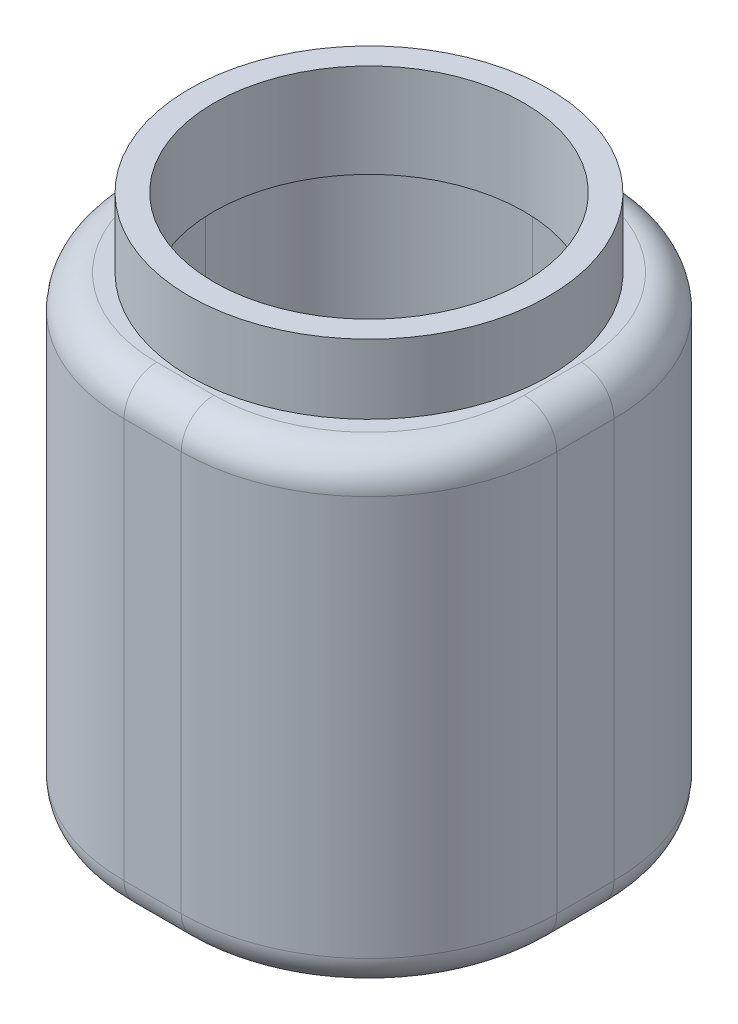
SolidWorks part; units mm, degrees
material "Glass"
ref_plane "Front Plane" through (0, 0, 0) normal (0, 0, 1) x (1, 0, 0)
ref_plane "Top Plane" through (0, 0, 0) normal (0, 1, 0) x (1, 0, 0)
ref_plane "Right Plane" through (0, 0, 0) normal (1, 0, 0) x (0, 0, -1)
sketch "Sketch1" plane through (0, 0, 0) normal (0, 1, 0) x (1, 0, 0)
  line L1 (-67.31, 67.31) -> (67.31, 67.31)
  line L2 (-67.31, 67.31) -> (-67.31, -67.31)
  line L3 (-67.31, -67.31) -> (67.31, -67.31)
  line L4 (67.31, 67.31) -> (67.31, -67.31)
  line L5 (-67.31, 67.31) -> (67.31, -67.31) construction
  line L6 (-67.31, -67.31) -> (67.31, 67.31) construction
  point P0 (0, 0)
  dimension "D1" = 134.62
extrude "Boss-Extrude1" add sketch "Sketch1" along normal blind 144.78
fillet "Fillet1" radius 58.42 4 edges at (67.31, 72.39, 67.31) (-67.31, 72.39, 67.31) (67.31, 72.39, -67.31) (-67.31, 72.39, -67.31)
fillet "Fillet2" radius 10.16 16 edges at (0, 144.78, -67.31) (50.1992, 144.78, -50.1992) (67.31, 144.78, 0) (50.1992, 144.78, 50.1992) (0, 144.78, 67.31) (-50.1992, 144.78, 50.1992) (-67.31, 144.78, 0) (-67.31, 0, 0) (-50.1992, 0, 50.1992) (0, 0, 67.31) (50.1992, 0, 50.1992) (67.31, 0, 0) (50.1992, 0, -50.1992) (0, 0, -67.31) (-50.1992, 144.78, -50.1992) (-50.1992, 0, -50.1992)
sketch "Sketch2" plane through (0, 144.78, 0) normal (0, 1, 0) x (1, 0, 0)
  circle A0 centre (0, 0) radius 55.88
  dimension "D1" = 111.76
extrude "Boss-Extrude2" add sketch "Sketch2" along normal blind 21.59
shell "Shell1" thickness 7.62
